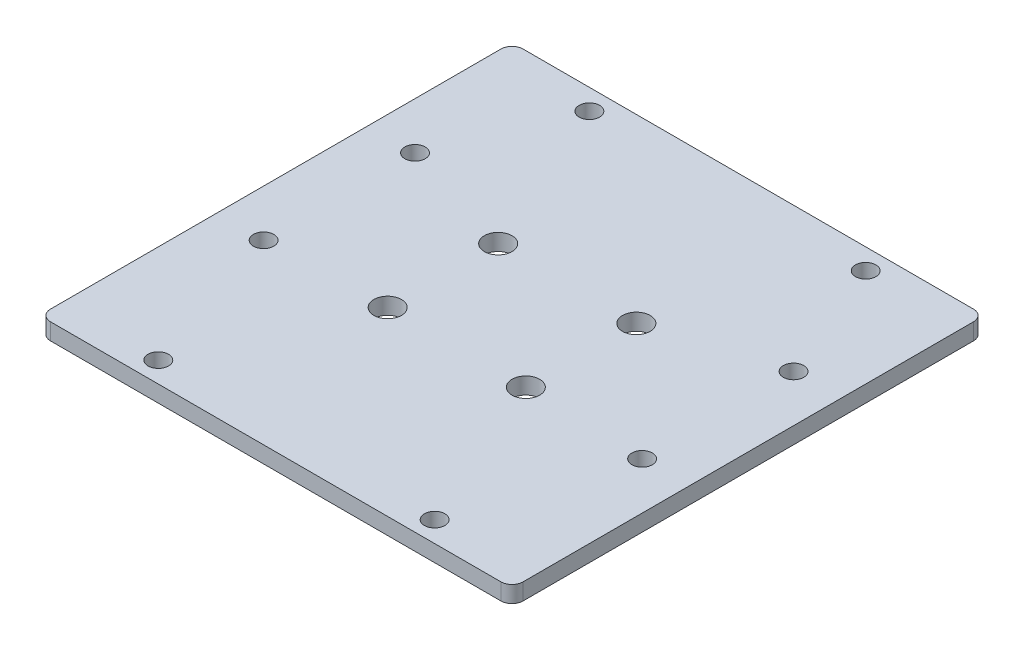
SolidWorks part; units mm, degrees
material "Acrylic (Medium-high impact)"
ref_plane "Front Plane" through (0, 0, 0) normal (0, 0, 1) x (1, 0, 0)
ref_plane "Top Plane" through (0, 0, 0) normal (0, 1, 0) x (1, 0, 0)
ref_plane "Right Plane" through (0, 0, 0) normal (1, 0, 0) x (0, 0, -1)
sketch "Sketch1" plane through (0, 0, 0) normal (0, 1, 0) x (1, 0, 0)
  line L1 (42.75, -42.75) -> (-42.75, -42.75)
  line L2 (42.75, -42.75) -> (42.75, 42.75)
  line L3 (42.75, 42.75) -> (-42.75, 42.75)
  line L4 (-42.75, -42.75) -> (-42.75, 42.75)
  line L5 (42.75, -42.75) -> (-42.75, 42.75) construction
  line L6 (42.75, 42.75) -> (-42.75, -42.75) construction
  point P0 (0, 0)
  dimension "D1" = 85.5
  dimension "D2" = 85.5
extrude "Boss-Extrude1" add sketch "Sketch1" along normal blind 3
fillet "Fillet1" radius 2 4 edges at (-42.75, 1.5, -42.75) (42.75, 1.5, -42.75) (-42.75, 1.5, 42.75) (42.75, 1.5, 42.75)
sketch "Sketch3" plane through (0, 3, 0) normal (0, 1, 0) x (1, 0, 0)
  circle A4 centre (-25, 39) radius 1.85
  circle A5 centre (25, 39) radius 1.85
  circle A6 centre (25, -39) radius 1.85
  circle A7 centre (-25, -39) radius 1.85
  dimension "D1" = 3.7
extrude "Cut-Extrude1" cut sketch "Sketch3" against normal blind 10
sketch "Sketch4" plane through (0, 3, 0) normal (0, 1, 0) x (1, 0, 0)
  line L0 (12.5, 10) -> (-12.5, -10) construction
  line L1 (12.5, -10) -> (-12.5, 10) construction
  circle A4 centre (-12.5, 10) radius 2.5
  circle A5 centre (-12.5, -10) radius 2.5
  circle A6 centre (12.5, 10) radius 2.5
  circle A7 centre (12.5, -10) radius 2.5
  circle A8 centre (-34.25, 16.7) radius 1.85
  circle A9 centre (-34.25, -10.7) radius 1.85
  circle A10 centre (34.25, -10.7) radius 1.85
  circle A11 centre (34.25, 16.7) radius 1.85
  dimension "D1" = 5
  dimension "D2" = 5
  dimension "D3" = 5
  dimension "D4" = 5
  dimension "D5" = 3.7
extrude "Cut-Extrude2" cut sketch "Sketch4" against normal blind 10
